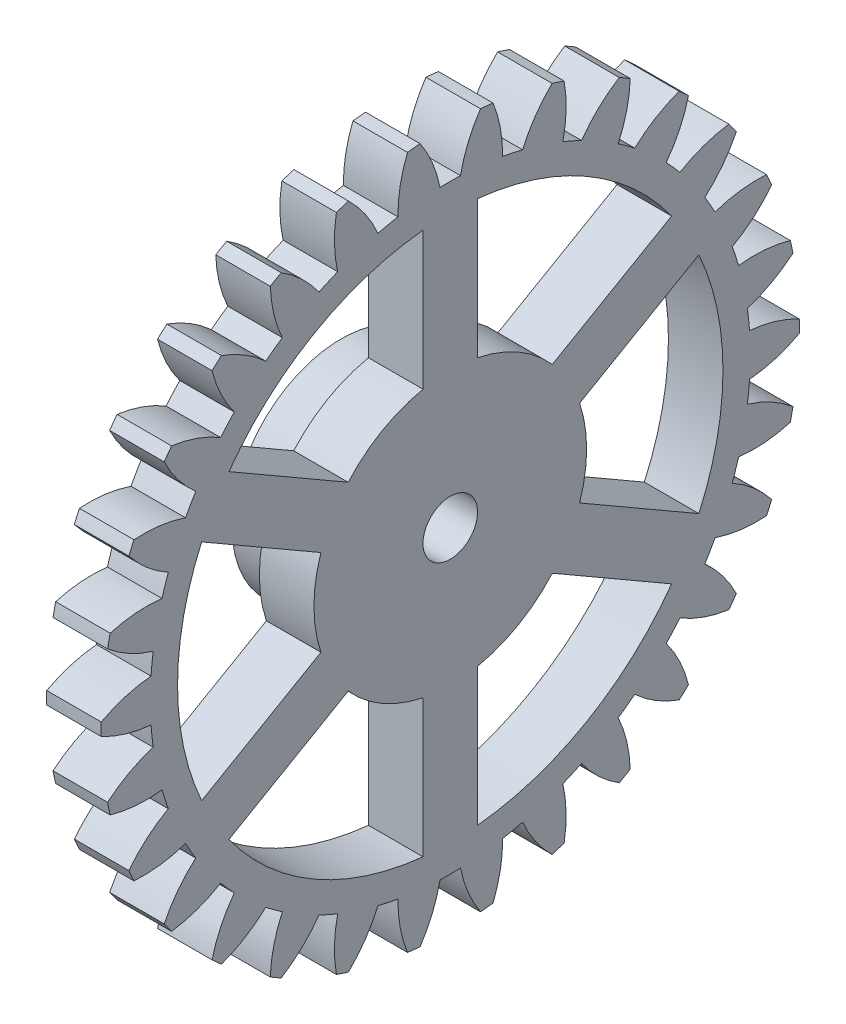
SolidWorks part; units mm, degrees
ref_plane "Plane1" through (0, 0, 0) normal (0, 0, 1) x (1, 0, 0)
ref_plane "Plane2" through (0, 0, 0) normal (0, 1, 0) x (1, 0, 0)
ref_plane "Plane3" through (0, 0, 0) normal (1, 0, 0) x (0, 0, -1)
sketch "HoldingSke" plane through (0, 0, 0) normal (0, 1, 0) x (1, 0, 0)
  line L0 (0, 0) -> (219.9705, -127)
  line L1 (-15, 0) -> (100, 0) construction
  line L2 (0, 0) -> (-2.1039, 2.3779)
  line L3 (0, 0) -> (-11.863, 4.5341)
  line L4 (0, 0) -> (7.479, 4.318)
  line L5 (0, 0) -> (-11.8993, -4.4381)
  line L6 (0, 0) -> (-5.2639, -3.5516)
  line L7 (-2.1039, 2.3779) -> (0.6298, 14.7802)
  line L8 (-76.2, 54.61) -> (-69.596, 54.61)
  line L9 (-71.009, 38.7566) -> (-53.1078, 45.2721)
  line L10 (-76.2, 71.12) -> (104.1128, 71.12)
  line L11 (0, 0) -> (-6.35, 0)
  line L12 (-76.2, 101.6) -> (-76.0984, 101.6)
  line L13 (24.9733, 27.94) -> (52.9518, 28.4284)
  line L14 (24.9733, 27.94) -> (24.9746, 27.94)
  line L15 (24.9733, 27.94) -> (100.4006, 29.5858)
  circle A0 centre (0, 0) radius 3.175
  circle A1 centre (0, 0) radius 12.7
  circle A2 centre (0, 0) radius 12.7
  circle A3 centre (0, 0) radius 3.175
  dimension "MHD" = 25.4
  dimension "Hub_dia" = 25.4
  dimension "Bore" = 6.35
  dimension "MBD" = 6.35
  dimension "Num_teeth" = 30
  dimension "Pitch" = 254
  dimension "Overall_len" = 12.7
  dimension "Show_teeth" = 30
  dimension "Thickness" = 6.35
  dimension "OAL" = 12.7001
  dimension "T_dim" = 6.604
  dimension "Ap" = 20
  dimension "H" = 19.05
  dimension "Pitch_radius" = 180.3128
  dimension "Width" = 6.35
  dimension "Backlash" = 0.1016
  dimension "Addendum_fac" = 1
  dimension "Dedendum_fac" = 1.25
  dimension "Clearance_fac" = 0.25
  dimension "Dedendum_add" = 0.0013
sketch "BasProSke" plane through (0, 0, 0) normal (0, 1, 0) x (1, 0, 0)
  line L0 (-10, 0) -> (60, 0) construction
  line L1 (0, 0) -> (0, 40.64)
  line L2 (0, 0) -> (6.35, 0)
  line L3 (6.35, 0) -> (6.35, 40.64)
  line L4 (6.35, 40.64) -> (0, 40.64)
  dimension "Thickness" = 6.35
  dimension "Diameter" = 81.28
revolve "Base-Revolve" add sketch "BasProSke" angle 360 about L0
sketch "TooCutSke" plane through (0, 0, 0) normal (1, 0, 0) x (0, 0, -1)
  line L1 (0, 0) -> (0, 107) construction
  line L2 (0, 0) -> (-2.1718, 38.0381) construction
  line L3 (0, 0) -> (-7.956, 75.6964) construction
  line L4 (-2.1718, 38.0381) -> (-3.978, 37.8482) construction
  arc A0 (1.1931, 34.9033) -> (-1.1931, 34.9033) centre (0, 0) ccw
  arc A1 (3.5338, 40.5116) -> (-3.5338, 40.5116) centre (0, 0) ccw
  circle A2 centre (0, 0) radius 38.1 construction
  circle A3 centre (0, 0) radius 35.8023 construction
  arc A4 (-1.1931, 34.9033) -> (-3.5338, 40.5116) centre (-16.1452, 31.9552) ccw
  arc A5 (3.5338, 40.5116) -> (1.1931, 34.9033) centre (16.1452, 31.9552) ccw
  dimension "Root_dia" = 69.8475
  dimension "Overcut_dia" = 81.3308
  dimension "Pitch_dia" = 76.2
  dimension "Base_dia" = 71.6046
  dimension "Flank_rad" = 15.24
  dimension "Half_ang" = 6
  dimension "Half_CT" = 1.8162
extrude "ToothCut" cut sketch "TooCutSke" along normal through all
fillet "Breaks" [suppressed] radius 0.0508
fillet "RootFillets" [suppressed] radius 0.6363
pattern_circular "TeethCuts" count 30 every 12 about axis through (-10, 0, 0) along (1, 0, 0) of "ToothCut", "RootFillets", "Breaks"
sketch "HubNeaOneSke" plane through (0, 0, 0) normal (-1, 0, 0) x (0, 0, 1)
  circle A0 centre (0, 0) radius 12.7
  dimension "Diameter" = 25.4
extrude "HubNearOne" add sketch "HubNeaOneSke" along normal blind 6.3501
sketch "HubNeaBotSke" plane through (0, 0, 0) normal (-1, 0, 0) x (0, 0, 1)
  circle A0 centre (0, 0) radius 12.7
  dimension "Diameter" = 25.4
extrude "HubNearBoth" [suppressed] add sketch "HubNeaBotSke" along normal blind 3.175
ref_plane "FarPln" through (6.35, 0, 0) normal (1, 0, 0) x (0, 0, -1)
sketch "HubFarSke" plane through (6.35, 0, 0) normal (1, 0, 0) x (0, 0, -1)
  circle A0 centre (0, 0) radius 12.7
  dimension "Diameter" = 25.4
extrude "HubFar" [suppressed] add sketch "HubFarSke" along normal blind 3.175
sketch "BorSke" plane through (0, 0, 0) normal (1, 0, 0) x (0, 0, -1)
  circle A0 centre (0, 0) radius 3.175
  dimension "Diameter" = 6.35
extrude "Bore" cut sketch "BorSke" along normal mid plane 25.4001
sketch "KeySke" plane through (0, 0, 0) normal (1, 0, 0) x (0, 0, -1)
  line L0 (-0.127, 0) -> (-0.127, 3.429)
  line L1 (-0.127, 3.429) -> (0.127, 3.429)
  line L2 (0.127, 3.429) -> (0.127, 0)
  line L3 (0, 0) -> (0, 34) construction
  line L4 (-0.127, 0) -> (0.127, 0)
  dimension "Offset" = 3.429
  dimension "Width" = 0.254
extrude "Keyway" [suppressed] cut sketch "KeySke" along normal mid plane 25.4001
pattern_circular "Keyway2" [suppressed] count 2 every 90 about axis through (-10, 0, 0) along (1, 0, 0)
sketch "Sketch1" plane through (-6.3501, 0, 0) normal (-1, 0, 0) x (0, 0, 1)
  line L0 (0, 12.7) -> (0, 34.9237)
  line L1 (30.2448, 17.4619) -> (10.9985, 6.35)
  line L2 (10.9985, 6.35) -> (0, 0) construction
  line L3 (0, 0) -> (0, 12.7) construction
  line L4 (3.175, 15.5543) -> (3.175, 31.5896)
  line L5 (25.7699, 18.5444) -> (11.8829, 10.5268)
  arc A0 (0, 34.9237) -> (30.2448, 17.4619) centre (0, 0) cw
  arc A1 (10.9985, 6.35) -> (0, 12.7) centre (0, 0) ccw
  arc A2 (1.1931, 34.9033) -> (-1.1931, 34.9033) centre (0, 0) ccw construction
  circle A3 centre (0, 0) radius 12.7 construction
  arc A4 (11.8829, 10.5268) -> (3.175, 15.5543) centre (0, 0) ccw
  arc A5 (3.175, 31.5896) -> (25.7699, 18.5444) centre (0, 0) cw
  point P4 (22.0177, 16.6468)
  point P7 (-20.5513, 18.0323)
  point P8 (13.7344, 10.8208)
  point P9 (0.1318, 32.1673)
  point P10 (0, 34.9237)
  point P14 (10.9985, 6.35)
  dimension "D1" = 60
  dimension "D2" = 3.175
extrude "Cut-Extrude2" cut sketch "Sketch1" against normal through all contours A5 L4 A4 L5
pattern_circular "CirPattern1" count 6 over 360 about axis through (0, 0, 0) along (1, 0, 0) of "Cut-Extrude2"
equation "' \"Pitch@HoldingSke\" = 4"
equation "' \"Num_teeth@HoldingSke\" = 12"
equation "' \"Ap@HoldingSke\" =  20"
equation "' \"Ap@HoldingSke\" = 20"
equation "' \"Width@HoldingSke\" = 0.5"
equation "' \"Hub_dia@HoldingSke\"= 1"
equation "' \"Hub_dia@HoldingSke\" = 1"
equation "' \"Overall_len@HoldingSke\" = 1.0"
equation "' \"Bore@HoldingSke\" = 0.75"
equation "' \"T_dim@HoldingSke\" = 0.85"
equation "' \"Width@KeySke\" = 0.25"
equation "' \"Show_teeth@HoldingSke\" = 13"
equation "' \"Backlash@HoldingSke\" = 0.009"
equation "' \"Addendum_fac@HoldingSke\" = 1.0"
equation "' \"Dedendum_fac@HoldingSke\" = 1.25"
equation "' \"Dedendum_add@HoldingSke\" = 0.00005"
equation "' \"Clearance_fac@HoldingSke\" = 0.25"
equation "' \"Pitch@HoldingSke\" = 0.5"
equation "' \"Num_teeth@HoldingSke\" = 23"
equation "' \"Show_teeth@HoldingSke\" = 23"
equation "' \"Backlash@HoldingSke\" = 0.0375"
equation "\"Overcut_dia@TooCutSke\" = (\"Num_teeth@HoldingSke\" + 2 * \"Addendum_fac@HoldingSke\") / \"Pitch@HoldingSke\" + 0.002"
equation "\"Pitch_dia@TooCutSke\" = \"Num_teeth@HoldingSke\" / \"Pitch@HoldingSke\""
equation "\"Base_dia@TooCutSke\" = \"Num_teeth@HoldingSke\" / \"Pitch@HoldingSke\" * cos((\"Ap@HoldingSke\"  * 3.14159265 / 180))"
equation "\"Root_dia@TooCutSke\" = (\"Num_teeth@HoldingSke\" + 2) / \"Pitch@HoldingSke\" - 2 * (\"Addendum_fac@HoldingSke\" + \"Dedendum_fac@HoldingSke\") / \"Pitch@HoldingSke\" - \"Dedendum_add@HoldingSke\" * 2"
equation "\"Half_ang@TooCutSke\" = 180 / \"Num_teeth@HoldingSke\""
equation "\"Half_CT@TooCutSke\" = \"Num_teeth@HoldingSke\" / \"Pitch@HoldingSke\" * sin((3.14159265 / 2 / \"Num_teeth@HoldingSke\")) / 2 - 7 * \"Backlash@HoldingSke\" / 4"
equation "\"Flank_rad@TooCutSke\" = \"Num_teeth@HoldingSke\" / \"Pitch@HoldingSke\" / 5"
equation "\"Radius@RootFillets\" = \"Clearance_fac@HoldingSke\" / \"Pitch@HoldingSke\" + \"Dedendum_add@HoldingSke\""
equation "\"Break_rad@Breaks\" = 0.02 / \"Pitch@HoldingSke\""
equation "\"Thickness@HoldingSke\" = \"Width@HoldingSke\""
equation "\"OAL@HoldingSke\" = \"Thickness@HoldingSke\""
equation "\"MHD@HoldingSke\" = (\"Num_teeth@HoldingSke\" + 2) / \"Pitch@HoldingSke\" - 2 * (\"Addendum_fac@HoldingSke\" + \"Dedendum_fac@HoldingSke\")  / \"Pitch@HoldingSke\" - \"Dedendum_add@HoldingSke\" * 2"
equation "\"MBD@HoldingSke\" = (\"Num_teeth@HoldingSke\" + 2) / \"Pitch@HoldingSke\" - 2 * (\"Addendum_fac@HoldingSke\" + \"Dedendum_fac@HoldingSke\")  / \"Pitch@HoldingSke\" - \"Dedendum_add@HoldingSke\" * 2 - 0.002"
equation "\"MHD@HoldingSke\" = ((sgn( \"MHD@HoldingSke\" - \"Hub_dia@HoldingSke\" )-1)*( \"MHD@HoldingSke\" - \"Hub_dia@HoldingSke\" ))/-2+ \"Hub_dia@HoldingSke\""
equation "\"MBD@HoldingSke\" = ((sgn( \"MBD@HoldingSke\" - \"Bore@HoldingSke\" )-1)*( \"MBD@HoldingSke\" - \"Bore@HoldingSke\" ))/-2+ \"Bore@HoldingSke\""
equation "\"OAL@HoldingSke\" = ((sgn( \"OAL@HoldingSke\" - \"Overall_len@HoldingSke\" )+1)*( \"OAL@HoldingSke\" - \"Overall_len@HoldingSke\" ))/2 + \"Overall_len@HoldingSke\" + 0.000002"
equation "\"Num_teeth@TeethCuts\" = int( \"Show_teeth@HoldingSke\" ) + 1"
equation "\"Num_teeth@TeethCuts\" = ((sgn( \"Num_teeth@TeethCuts\" - \"Num_teeth@HoldingSke\" )-1)*( \"Num_teeth@TeethCuts\" - \"Num_teeth@HoldingSke\" ))/-2+ \"Num_teeth@HoldingSke\""
equation "\"Num_teeth@TeethCuts\" = ((sgn( \"Num_teeth@TeethCuts\" - 2.0)+1)*( \"Num_teeth@TeethCuts\" - 2.0))/2 +2.0"
equation "\"Angle@TeethCuts\" = 360.0 / \"Num_teeth@HoldingSke\""
equation "\"Diameter@BasProSke\" = (\"Num_teeth@HoldingSke\" + 2 * \"Addendum_fac@HoldingSke\") / \"Pitch@HoldingSke\""
equation "\"Thickness@BasProSke\"  = \"Thickness@HoldingSke\""
equation "' \"Fillet_rad@BasProSke\" =  \"Thickness@HoldingSke\" * 0.05"
equation "' \"Fillet_rad@BasProSke\" = \"Thickness@HoldingSke\" * 0.05"
equation "\"MHD@HoldingSke\" = ((sgn( \"MHD@HoldingSke\" - \"Root_dia@TooCutSke\" )-1)*( \"MHD@HoldingSke\" - \"Root_dia@TooCutSke\" ))/-2+ \"Root_dia@TooCutSke\""
equation "\"Diameter@HubNeaOneSke\" = \"MHD@HoldingSke\""
equation "\"Length@HubNearOne\" = \"OAL@HoldingSke\" - \"Thickness@BasProSke\""
equation "\"Diameter@HubNeaBotSke\" = \"MHD@HoldingSke\""
equation "\"Length@HubNearBoth\" = ( \"OAL@HoldingSke\" - \"Thickness@BasProSke\" ) / 2.0"
equation "\"Thickness@FarPln\" = \"Thickness@BasProSke\""
equation "\"Diameter@HubFarSke\" = \"MHD@HoldingSke\""
equation "\"Length@HubFar\" = ( \"OAL@HoldingSke\" - \"Thickness@BasProSke\" ) / 2.0"
equation "\"Diameter@BorSke\" = \"MBD@HoldingSke\""
equation "\"D1@Bore\" = \"OAL@HoldingSke\" * 2.0"
equation "\"D1@Keyway\" = \"OAL@HoldingSke\" * 2.0"
equation "\"Offset@KeySke\" = \"T_dim@HoldingSke\" - \"MBD@HoldingSke\" / 2.0"
